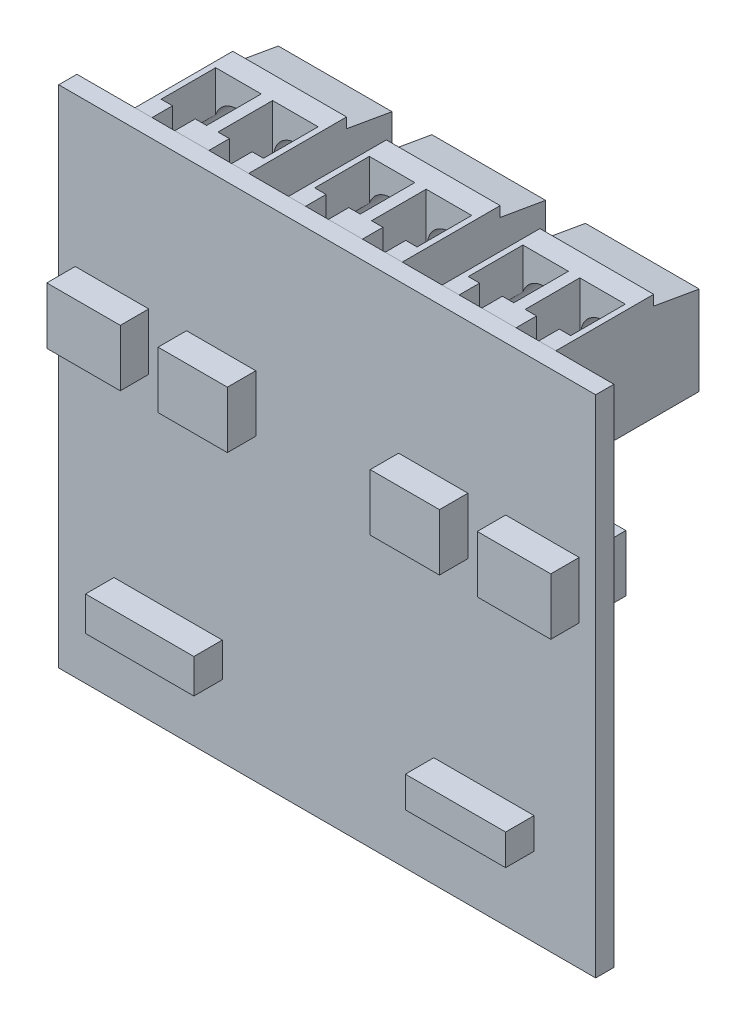
SolidWorks part; units mm, degrees
ref_plane "Front Plane" through (0, 0, 0) normal (0, 0, 1) x (1, 0, 0)
ref_plane "Top Plane" through (0, 0, 0) normal (0, 1, 0) x (1, 0, 0)
ref_plane "Right Plane" through (0, 0, 0) normal (1, 0, 0) x (0, 0, -1)
sketch "Sketch1" plane through (0, 0, 0) normal (0, 0, 1) x (1, 0, 0)
  line L1 (-23.6, -22.2) -> (23.6, -22.2)
  line L2 (-23.6, -22.2) -> (-23.6, 22.2)
  line L3 (-23.6, 22.2) -> (23.6, 22.2)
  line L4 (23.6, -22.2) -> (23.6, 22.2)
  line L5 (-23.6, -22.2) -> (23.6, 22.2) construction
  line L6 (-23.6, 22.2) -> (23.6, -22.2) construction
  point P0 (0, 0)
  dimension "D1" = 47.2
  dimension "D2" = 44.4
extrude "Boss-Extrude1" add sketch "Sketch1" against normal blind 1.6
sketch "Sketch3" plane through (0, 22.2, 0) normal (0, 1, 0) x (1, 0, 0)
  line L0 (0, 1.6) -> (0, 10.6761) construction
  line L1 (23.6, 1.6) -> (-23.6, 1.6) construction
  line L2 (18.5, 1.6) -> (18.5, 14.2)
  line L3 (-18.5, 1.6) -> (-18.5, 14.2)
  line L4 (18.5, 1.6) -> (8.5, 1.6)
  line L5 (18.5, 14.2) -> (8.5, 14.2)
  line L6 (-18.5, 1.6) -> (-18.5, 10.6761) construction
  line L7 (18.5, 1.6) -> (18.5, 10.6761) construction
  line L8 (-8.5, 1.6) -> (-8.5, 14.2)
  line L9 (8.5, 1.6) -> (8.5, 14.2)
  line L10 (5, 1.6) -> (5, 14.2)
  line L11 (-5, 1.6) -> (-5, 14.2)
  line L12 (-5, 1.6) -> (-5, 10.6761) construction
  line L13 (5, 1.6) -> (5, 10.6761) construction
  line L14 (-8.5, 14.2) -> (-18.5, 14.2)
  line L15 (23.6, 14.2) -> (-23.6, 14.2) construction
  line L16 (5, 14.2) -> (-5, 14.2)
  line L17 (23.6, 1.6) -> (-23.6, 1.6) construction
  line L18 (-8.5, 1.6) -> (-18.5, 1.6)
  line L19 (5, 1.6) -> (-5, 1.6)
  dimension "D1" = 18.5
  dimension "D2" = 18.5
  dimension "D3" = 12.6
  dimension "D4" = 10
  dimension "D5" = 10
  dimension "D6" = 5
  dimension "D7" = 5
extrude "Boss-Extrude2" add sketch "Sketch3" against normal blind 9.4 separate body
sketch "Sketch4" plane through (0, 0, -14.2) normal (0, 0, -1) x (-1, 0, 0)
  line L0 (-16.1, 14.4) -> (-10.9, 14.4) construction
  line L1 (-23.6, 22.2) -> (23.6, 22.2) construction
  line L2 (-18.5, 12.8) -> (-18.5, 22.2) construction
  line L3 (-16.1, 14.4) -> (-16.1, 18) construction
  line L4 (-8.5, 17.5) -> (-5, 17.5) construction
  line L5 (-8.5, 12.8) -> (-8.5, 22.2) construction
  line L6 (-5, 12.8) -> (-5, 22.2) construction
  line L7 (5, 17.5) -> (8.5, 17.5) construction
  line L8 (5, 12.8) -> (5, 22.2) construction
  line L9 (8.5, 12.8) -> (8.5, 22.2) construction
  line L10 (-6.75, 17.5) -> (-6.75, 22.2) construction
  line L11 (6.75, 17.5) -> (6.75, 22.2) construction
  line L12 (-18.5, 12.8) -> (-8.5, 12.8) construction
  circle A0 centre (-16.1, 14.4) radius 0.9
  circle A1 centre (-10.9, 14.4) radius 0.9
  circle A2 centre (-16.1, 18) radius 2
  circle A3 centre (-10.9, 18) radius 2
  circle A4 centre (2.6, 18) radius 2
  circle A5 centre (2.6, 14.4) radius 0.9
  circle A6 centre (-2.6, 14.4) radius 0.9
  circle A7 centre (-2.6, 18) radius 2
  circle A8 centre (16.1, 14.4) radius 0.9
  circle A9 centre (16.1, 18) radius 2
  circle A10 centre (10.9, 14.4) radius 0.9
  circle A11 centre (10.9, 18) radius 2
  dimension "D1" = 1.8
  dimension "D2" = 1.8
  dimension "D3" = 1.6
  dimension "D4" = 5.2
  dimension "D5" = 2.4
  dimension "D6" = 4
  dimension "D8" = 4
  dimension "D9" = 3.6
  dimension "D7" = 3.6
extrude "Cut-Extrude1" cut sketch "Sketch4" against normal blind 12.6
sketch "Sketch5" plane through (-18.5, 0, 0) normal (-1, 0, 0) x (0, 0, 1)
  line L4 (-14.2, 20.6) -> (-14.2, 22.2)
  line L5 (-10.2, 22.2) -> (-10.2, 21.3)
  line L6 (-14.2, 22.2) -> (-10.2, 22.2)
  line L9 (-14.2, 20.6) -> (-10.2, 21.3)
extrude "Cut-Extrude2" cut sketch "Sketch5" against normal up to surface (37 mm away)
sketch "Sketch6" plane through (0, 22.2, 0) normal (0, 1, 0) x (1, 0, 0)
  line L0 (-12, 1.6) -> (-10, 1.6)
  line L1 (-18.5, 1.6) -> (-8.5, 1.6) construction
  line L2 (-8.5, 10.2) -> (-5, 10.2) construction
  line L3 (-18.5, 1.6) -> (-8.5, 1.6) construction
  line L4 (-6.75, 10.2) -> (-6.75, 1.6) construction
  line L5 (23.6, 1.6) -> (-23.6, 1.6) construction
  line L6 (8.5, 10.2) -> (5, 10.2) construction
  line L7 (-17, 1.6) -> (-15, 1.6)
  line L8 (-9, 8.2) -> (-13, 8.2)
  line L9 (-18, 3.4) -> (-17, 3.4)
  line L10 (-18, 8.2) -> (-18, 3.4)
  line L11 (-9, 3.4) -> (-9, 8.2)
  line L12 (-13.5, 10.2) -> (-13.5, 1.6) construction
  line L13 (-14, 8.2) -> (-14, 3.4)
  line L14 (-13, 8.2) -> (-13, 3.4)
  line L15 (-17, 3.4) -> (-17, 1.6)
  line L16 (-10, 1.6) -> (-10, 3.4)
  line L17 (-15, 3.4) -> (-15, 1.6)
  line L18 (-12, 3.4) -> (-12, 1.6)
  line L19 (-18, 10.2) -> (-18, 1.6) construction
  line L20 (-17, 10.2) -> (-17, 1.6) construction
  line L21 (5, 10.2) -> (-5, 10.2) construction
  line L22 (-18.5, 3.4) -> (-8.5, 3.4) construction
  line L23 (-15, 3.4) -> (-14, 3.4)
  line L24 (-12, 10.2) -> (-12, 1.6) construction
  line L25 (-13, 10.2) -> (-13, 1.6) construction
  line L26 (-14, 10.2) -> (-14, 1.6) construction
  line L27 (-15, 10.2) -> (-15, 1.6) construction
  line L28 (-10, 1.6) -> (-10, 10.2) construction
  line L29 (-9, 1.6) -> (-9, 10.2) construction
  line L30 (-10, 3.4) -> (-9, 3.4)
  line L31 (-14, 8.2) -> (-18, 8.2)
  line L32 (-13, 3.4) -> (-12, 3.4)
  line L33 (6.75, 10.2) -> (6.75, 1.6) construction
  line L34 (-0.5, 3.4) -> (-1.5, 3.4)
  line L35 (0.5, 8.2) -> (4.5, 8.2)
  line L36 (-3.5, 3.4) -> (-4.5, 3.4)
  line L37 (1.5, 3.4) -> (0.5, 3.4)
  line L38 (-1.5, 3.4) -> (-1.5, 1.6)
  line L39 (1.5, 3.4) -> (1.5, 1.6)
  line L40 (-3.5, 1.6) -> (-3.5, 3.4)
  line L41 (3.5, 3.4) -> (3.5, 1.6)
  line L42 (-0.5, 8.2) -> (-0.5, 3.4)
  line L43 (0.5, 8.2) -> (0.5, 3.4)
  line L44 (-4.5, 3.4) -> (-4.5, 8.2)
  line L45 (4.5, 8.2) -> (4.5, 3.4)
  line L46 (4.5, 3.4) -> (3.5, 3.4)
  line L47 (-4.5, 8.2) -> (-0.5, 8.2)
  line L48 (3.5, 1.6) -> (1.5, 1.6)
  line L49 (-1.5, 1.6) -> (-3.5, 1.6)
  line L50 (15, 1.6) -> (17, 1.6)
  line L51 (10, 1.6) -> (12, 1.6)
  line L52 (18, 8.2) -> (14, 8.2)
  line L53 (9, 3.4) -> (10, 3.4)
  line L54 (9, 8.2) -> (9, 3.4)
  line L55 (18, 3.4) -> (18, 8.2)
  line L56 (13, 8.2) -> (13, 3.4)
  line L57 (14, 8.2) -> (14, 3.4)
  line L58 (10, 3.4) -> (10, 1.6)
  line L59 (17, 1.6) -> (17, 3.4)
  line L60 (12, 3.4) -> (12, 1.6)
  line L61 (15, 3.4) -> (15, 1.6)
  line L62 (12, 3.4) -> (13, 3.4)
  line L63 (17, 3.4) -> (18, 3.4)
  line L64 (13, 8.2) -> (9, 8.2)
  line L65 (14, 3.4) -> (15, 3.4)
  dimension "D2" = 1.8
  dimension "D5" = 0.5
  dimension "D6" = 0.5
  dimension "D7" = 1
  dimension "D8" = 1
  dimension "D9" = 1
  dimension "D10" = 1
extrude "Cut-Extrude3" cut sketch "Sketch6" against normal blind 8.4
sketch "Sketch7" plane through (0, 0, -1.6) normal (0, 0, -1) x (-1, 0, 0)
  line L0 (0, 12.8) -> (0, 0) construction
  line L1 (-5, 12.8) -> (5, 12.8) construction
  circle A0 centre (0, 9.3) radius 3.25
  circle A1 centre (0, 1.3) radius 3.25
  dimension "D1" = 6.5
  dimension "D2" = 3.5
  dimension "D3" = 8
  dimension "D4" = 6.5
extrude "Boss-Extrude3" add sketch "Sketch7" along normal blind 11.4 separate body
sketch "Sketch8" plane through (0, 0, -1.6) normal (0, 0, -1) x (-1, 0, 0)
  line L0 (0, 9.3) -> (0, 1.3) construction
  line L1 (-22.15, 9.0908) -> (-15.6896, 9.0908)
  line L2 (-22.15, 9.0908) -> (-22.15, 4.107)
  line L3 (-22.15, 4.107) -> (-15.6896, 4.107)
  line L4 (-15.6896, 9.0908) -> (-15.6896, 4.107)
  line L5 (-22.15, 9.0908) -> (-15.6896, 4.107) construction
  line L6 (-22.15, 4.107) -> (-15.6896, 9.0908) construction
  line L7 (-12.3671, 9.0908) -> (-6.2758, 9.0908)
  line L8 (-12.3671, 9.0908) -> (-12.3671, 4.107)
  line L9 (-12.3671, 4.107) -> (-6.2758, 4.107)
  line L10 (-6.2758, 9.0908) -> (-6.2758, 4.107)
  line L11 (22.15, 4.107) -> (15.6896, 9.0908) construction
  line L12 (22.15, 9.0908) -> (15.6896, 4.107) construction
  line L13 (6.2758, 9.0908) -> (6.2758, 4.107)
  line L14 (12.3671, 9.0908) -> (12.3671, 4.107)
  line L15 (12.3671, 9.0908) -> (6.2758, 9.0908)
  line L16 (15.6896, 9.0908) -> (15.6896, 4.107)
  line L17 (22.15, 4.107) -> (15.6896, 4.107)
  line L18 (22.15, 9.0908) -> (22.15, 4.107)
  line L19 (22.15, 9.0908) -> (15.6896, 9.0908)
  line L20 (12.3671, 4.107) -> (6.2758, 4.107)
  point P0 (-18.9198, 6.5989)
  point P21 (18.9198, 6.5989)
extrude "Boss-Extrude4" add sketch "Sketch8" along normal blind 2.5 separate body
ref_plane "Plane1" through (0, 0, 0) normal (-1, 0, 0) x (0, 0, 1)
sketch "Sketch9" plane through (0, 0, 0) normal (-1, 0, 0) x (0, 0, 1)
  line L0 (-1.7059, -18.6841) -> (-3.5367, -18.6841)
  line L1 (-3.5367, -18.6841) -> (-3.5367, -19.0996)
  line L2 (-3.5367, -20.515) -> (-1.7059, -20.515)
  line L3 (-1.7059, -20.515) -> (-1.7059, -18.6841)
  line L5 (-4.9339, -20.0996) -> (-4.9339, -24.4658) construction
  line L6 (-3.5367, -19.0996) -> (-4.4339, -19.0996)
  line L7 (-5.4339, -20.0996) -> (-5.4339, -24.4658)
  line L8 (-3.5367, -19.0996) -> (-4.4339, -19.0996)
  line L9 (-4.4339, -20.0996) -> (-4.4339, -24.4658)
  line L10 (-3.5367, -20.0996) -> (-4.4339, -20.0996)
  line L11 (-4.4339, -24.4658) -> (-5.4339, -24.4658)
  line L12 (-3.5367, -20.0996) -> (-3.5367, -20.515)
  line L13 (-3.5367, -19.5996) -> (-4.4339, -19.5996) construction
  arc A0 (-4.4339, -19.5996) -> (-4.9339, -20.0996) centre (-4.4339, -20.0996) ccw construction
  arc A1 (-4.4339, -19.0996) -> (-5.4339, -20.0996) centre (-4.4339, -20.0996) ccw
  dimension "D1" = 0.5
  dimension "D2" = 0.5
  dimension "D4" = 0.5
extrude "Boss-Extrude5" add sketch "Sketch9" along normal mid plane 30 separate body contours L10 L9 L11 L7 A1 L6 L1 L0 L3 L2 L12
sketch "Sketch10" plane through (0, 0, -5.4339) normal (0, 0, -1) x (-1, 0, 0)
  line L0 (0, -20.0996) -> (0, -24.5173) construction
  line L1 (15, -20.0996) -> (-15, -20.0996) construction
  line L2 (0, -0.88) -> (0, 0.88) construction
  line L3 (-3.5, -24.4658) -> (-3.5, -24.5173)
  line L4 (3.5, -19.0996) -> (3.5, -24.4658)
  line L5 (4, -19.0996) -> (4, -24.4658)
  line L6 (6, -19.0996) -> (6, -24.4658)
  line L7 (6.5, -19.0996) -> (6.5, -24.4658)
  line L8 (8.5, -19.0996) -> (8.5, -24.4658)
  line L9 (9, -19.0996) -> (9, -24.4658)
  line L10 (11, -19.0996) -> (11, -24.4658)
  line L11 (11.5, -19.0996) -> (11.5, -24.4658)
  line L12 (13.5, -19.0996) -> (13.5, -24.4658)
  line L13 (14, -19.0996) -> (14, -24.4658)
  line L14 (2.5, -19.0996) -> (2.5, -24.4658)
  line L15 (15, -19.0996) -> (-15, -19.0996) construction
  line L16 (15, -19.0996) -> (14, -19.0996)
  line L17 (2.5, -20.0996) -> (2.5, -24.5173) construction
  line L18 (3.5, -20.0996) -> (3.5, -24.5173) construction
  line L19 (4, -20.0996) -> (4, -24.5173) construction
  line L20 (6, -20.0996) -> (6, -24.5173) construction
  line L21 (6.5, -20.0996) -> (6.5, -24.5173) construction
  line L22 (8.5, -20.0996) -> (8.5, -24.5173) construction
  line L23 (9, -20.0996) -> (9, -24.5173) construction
  line L24 (11, -20.0996) -> (11, -24.5173) construction
  line L25 (11.5, -20.0996) -> (11.5, -24.5173) construction
  line L26 (13.5, -20.0996) -> (13.5, -24.5173) construction
  line L27 (14, -20.0996) -> (14, -24.5173) construction
  line L28 (3.5, -19.0996) -> (2.5, -19.0996)
  line L29 (6, -19.0996) -> (4, -19.0996)
  line L30 (8.5, -19.0996) -> (6.5, -19.0996)
  line L31 (11, -19.0996) -> (9, -19.0996)
  line L32 (13.5, -19.0996) -> (11.5, -19.0996)
  line L33 (15, -20.0996) -> (15, -24.4658) construction
  line L35 (15, -19.0996) -> (15, -24.4658)
  line L37 (0, -24.4658) -> (-15, -24.4658)
  line L38 (3.5, -24.4658) -> (2.5, -24.4658)
  line L39 (6, -24.4658) -> (4, -24.4658)
  line L40 (8.5, -24.4658) -> (6.5, -24.4658)
  line L41 (11, -24.4658) -> (9, -24.4658)
  line L42 (13.5, -24.4658) -> (11.5, -24.4658)
  line L43 (-3.5, -20.0996) -> (-3.5, -24.5173) construction
  line L44 (-13.5, -24.4658) -> (-11.5, -24.4658)
  line L45 (-11, -24.4658) -> (-9, -24.4658)
  line L46 (-8.5, -24.4658) -> (-6.5, -24.4658)
  line L47 (-6, -24.4658) -> (-4, -24.4658)
  line L48 (-3.5, -24.4658) -> (-2.5, -24.4658)
  line L49 (-15, -24.4658) -> (-14, -24.4658)
  line L50 (-15, -19.0996) -> (-15, -24.4658)
  line L51 (-13.5, -19.0996) -> (-11.5, -19.0996)
  line L52 (-11, -19.0996) -> (-9, -19.0996)
  line L53 (-8.5, -19.0996) -> (-6.5, -19.0996)
  line L54 (-6, -19.0996) -> (-4, -19.0996)
  line L55 (-3.5, -19.0996) -> (-2.5, -19.0996)
  line L56 (-15, -19.0996) -> (-14, -19.0996)
  line L57 (-2.5, -19.0996) -> (-2.5, -24.4658)
  line L58 (-14, -19.0996) -> (-14, -24.4658)
  line L59 (-13.5, -19.0996) -> (-13.5, -24.4658)
  line L60 (-11.5, -19.0996) -> (-11.5, -24.4658)
  line L61 (-11, -19.0996) -> (-11, -24.4658)
  line L62 (-9, -19.0996) -> (-9, -24.4658)
  line L63 (-8.5, -19.0996) -> (-8.5, -24.4658)
  line L64 (-6.5, -19.0996) -> (-6.5, -24.4658)
  line L65 (-6, -19.0996) -> (-6, -24.4658)
  line L66 (-4, -19.0996) -> (-4, -24.4658)
  line L67 (-3.5, -19.0996) -> (-3.5, -24.4658)
  line L68 (15, -24.4658) -> (14, -24.4658)
  dimension "D12" = 1
  dimension "D3" = 0.5
  dimension "D4" = 2
  dimension "D5" = 0.5
  dimension "D6" = 2
  dimension "D7" = 0.5
  dimension "D8" = 2
  dimension "D9" = 0.5
  dimension "D10" = 2
  dimension "D11" = 0.5
extrude "Cut-Extrude4" cut sketch "Sketch10" against normal up to surface (1.8972 mm away) contours L51 L60 L44 L59 | L52 L62 L45 L61 | L53 L64 L46 L63 | L54 L66 L47 L65 | L67 L55 L57 L48 | L50 L56 L58 L49 | L16 L13 L68 L35 | L32 L11 L42 L12 | L31 L9 L41 L10 | L30 L7 L40 L8 | L29 L5 L39 L6 | L28 L14 L38 L4 up to face at (0, -20.3073, -3.5367)
sketch "Sketch11" plane through (0, 0, -5.4339) normal (0, 0, -1) x (-1, 0, 0)
  line L0 (-2.5, -19.0996) -> (-2.5, -18.6841) construction
  line L1 (15, -18.6841) -> (-15, -18.6841) construction
  line L3 (-2.5, -18.6841) -> (2.5, -18.6841)
  line L4 (-2.5, -18.6841) -> (-2.5, -24.4658)
  line L5 (-2.5, -24.4658) -> (2.5, -24.4658)
  line L6 (2.5, -18.6841) -> (2.5, -24.4658)
extrude "Cut-Extrude6" cut sketch "Sketch11" against normal up to vertex
ref_plane "Plane2" through (0, 0, -0.8) normal (0, 0, 1) x (1, 0, 0)
mirror "Mirror1" about plane through (0, 0, -0.8) normal (0, 0, 1) of "Boss-Extrude4"
sketch "Sketch12" plane through (0, 0, 0) normal (0, 0, 1) x (1, 0, 0)
  line L1 (-18.7438, -12.8863) -> (-9.2233, -12.8863)
  line L2 (-18.7438, -12.8863) -> (-18.7438, -15.8964)
  line L3 (-18.7438, -15.8964) -> (-9.2233, -15.8964)
  line L4 (-9.2233, -12.8863) -> (-9.2233, -15.8964)
extrude "Boss-Extrude6" add sketch "Sketch12" along normal blind 2.5 separate body
sketch "Sketch13" plane through (0, 0, 0) normal (0, 0, 1) x (1, 0, 0)
  line L1 (9.3703, -12.546) -> (18.1804, -12.546)
  line L2 (9.3703, -12.546) -> (9.3703, -15.2631)
  line L3 (9.3703, -15.2631) -> (18.1804, -15.2631)
  line L4 (18.1804, -12.546) -> (18.1804, -15.2631)
extrude "Boss-Extrude7" add sketch "Sketch13" along normal blind 2.5 separate body
